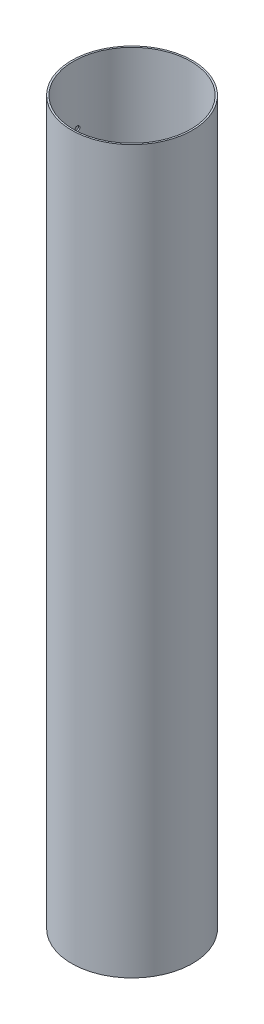
SolidWorks part; units mm, degrees
material "Wildman Fiberglass"
ref_plane "Front Plane" through (0, 0, 0) normal (0, 0, 1) x (1, 0, 0)
ref_plane "Top Plane" through (0, 0, 0) normal (0, 1, 0) x (1, 0, 0)
ref_plane "Right Plane" through (0, 0, 0) normal (1, 0, 0) x (0, 0, -1)
sketch "Sketch1" plane through (0, 0, 0) normal (0, 1, 0) x (1, 0, 0)
  circle A0 centre (0, 0) radius 49.657
  circle A1 centre (0, 0) radius 51.054
  dimension "D1" = 102.108
  dimension "D2" = 99.314
extrude "Boss-Extrude1" add sketch "Sketch1" along normal blind 609.6
extrude "Cut-Extrude1" cut sketch "Sketch2" against normal blind 12.7
sketch "Sketch2" plane through (122.9, 815.5954, -42.5514) normal (0.0679, 0, -0.9977) x (-0.9977, 0, -0.0679)
  circle A0 centre (119.7263, -256.7954) radius 1.9844
pattern_circular "CirPattern1" count 4 over 360 about axis through (0, 0, 0) along (0, 1, 0) of "Cut-Extrude1"
equation "\"Length\"=24"
equation "\"D1@Boss-Extrude1\"=\"Length\""
